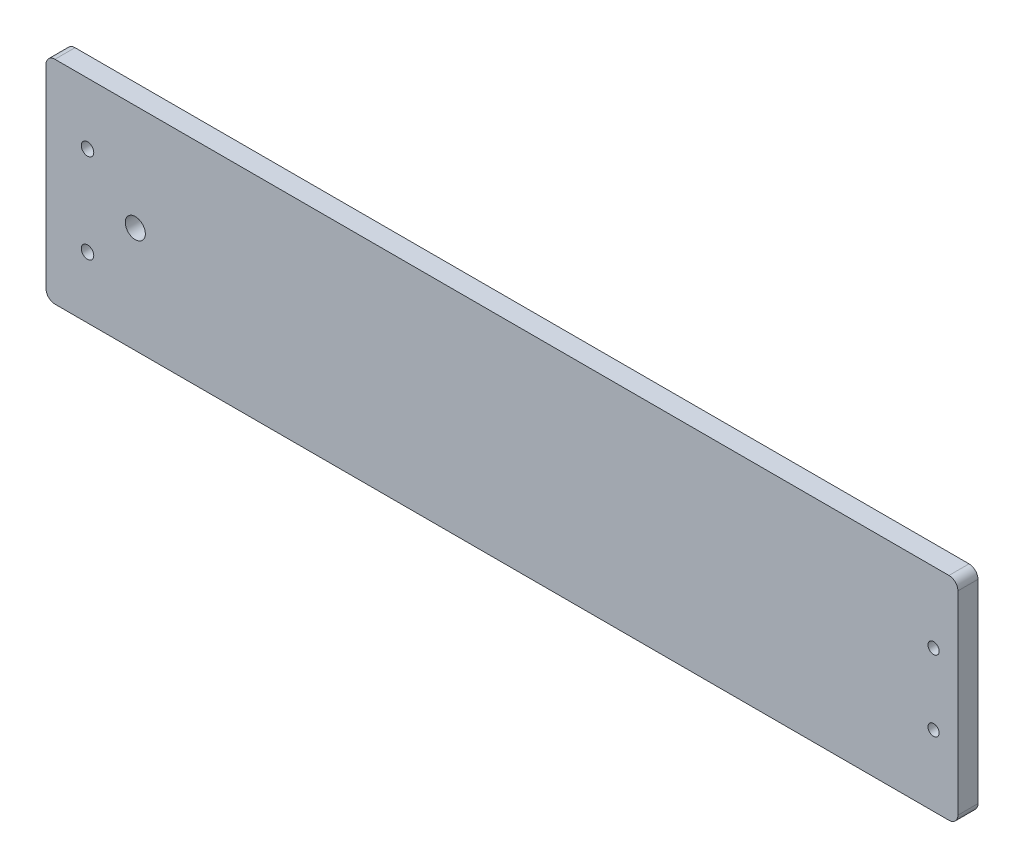
SolidWorks part; units mm, degrees
ref_plane "Front Plane" through (0, 0, 0) normal (0, 0, 1) x (1, 0, 0)
ref_plane "Top Plane" through (0, 0, 0) normal (0, 1, 0) x (1, 0, 0)
ref_plane "Right Plane" through (0, 0, 0) normal (1, 0, 0) x (0, 0, -1)
sketch "Sketch1" plane through (0, 0, 0) normal (0, 0, 1) x (1, 0, 0)
  line L0 (0, 23.75) -> (0, -23.75) construction
  line L1 (-102.12, -23.75) -> (102.12, -23.75)
  line L2 (-102.12, -23.75) -> (-102.12, 23.75)
  line L3 (-102.12, 23.75) -> (102.12, 23.75)
  line L4 (102.12, -23.75) -> (102.12, 23.75)
  dimension "D1" = 47.5
  dimension "D2" = 204.24
extrude "Boss-Extrude1" add sketch "Sketch1" along normal mid plane 4.5
hole_wizard "#8 Clearance Hole1" positions "Sketch2" profile "Sketch3" hole size "#8" standard "ANSI Inch" end condition up to next
sketch "Sketch2" plane through (0, 0, 2.25) normal (0, 0, 1) x (1, 0, 0)
  line L0 (-82.12, 0) -> (-102.12, 0) construction
  line L1 (-102.12, 23.75) -> (-102.12, -23.75) construction
  point P0 (-82.12, 0)
  dimension "D1" = 20
sketch "Sketch3" plane through (-82.12, 0, 2.25) normal (1, 0, 0) x (0, -1, 0)
  line L0 (0, 0) -> (0, 4.5)
  line L1 (0, 4.5) -> (2.2479, 4.5)
  line L2 (2.2479, 4.5) -> (2.2479, 0)
  line L5 (2.2479, 0) -> (0, 0)
  line L11 (0, -6.35) -> (0, 107.95) construction
  dimension "Thru Hole Dia." = 4.4958
  dimension "Thru Hole Depth" = 4.5
fillet "Fillet1" radius 2 4 edges at (-102.12, -23.75, 0) (102.12, -23.75, 0) (102.12, 23.75, 0) (-102.12, 23.75, 0)
hole_wizard "#3 Clearance Hole1" positions "Sketch4" profile "Sketch5" hole size "#3" standard "ANSI Inch" end condition up to next
sketch "Sketch4" plane through (0, 0, 2.25) normal (0, 0, 1) x (1, 0, 0)
  point P0 (-92.82, 10)
  point P2 (-92.82, -10)
  point P14 (-63.4457, 10)
  point P16 (-63.4457, -10)
sketch "Sketch5" plane through (-92.82, 10, 2.25) normal (1, 0, 0) x (0, -1, 0)
  line L0 (0, 0) -> (0, 4.5)
  line L1 (0, 4.5) -> (1.397, 4.5)
  line L2 (1.397, 4.5) -> (1.397, 0)
  line L5 (1.397, 0) -> (0, 0)
  line L11 (0, -6.35) -> (0, 107.95) construction
  dimension "Thru Hole Dia." = 2.794
  dimension "Thru Hole Depth" = 4.5
hole_wizard "#2 (0.221) Diameter Hole1" positions "Sketch6" profile "Sketch7" hole size "#2" standard "ANSI Inch"
sketch "Sketch6" plane through (0, 0, -2.25) normal (0, 0, -1) x (-1, 0, 0)
  point P0 (-96.6669, 7.9375)
  point P2 (-96.6669, -7.9375)
sketch "Sketch7" plane through (96.6669, 7.9375, -2.25) normal (1, 0, 0) x (0, 1, 0)
  line L0 (0, 0) -> (0, 20.7511)
  line L1 (0, 20.7511) -> (1.25, 20)
  line L2 (1.25, 20) -> (1.25, 0)
  line L5 (1.25, 0) -> (0, 0)
  line L10 (0, 20.7511) -> (-1.25, 20) construction
  line L11 (0, -6.35) -> (0, 107.95) construction
  dimension "Hole Dia." = 2.5
  dimension "Hole Depth" = 20
  dimension "Drill Angle" = 118
